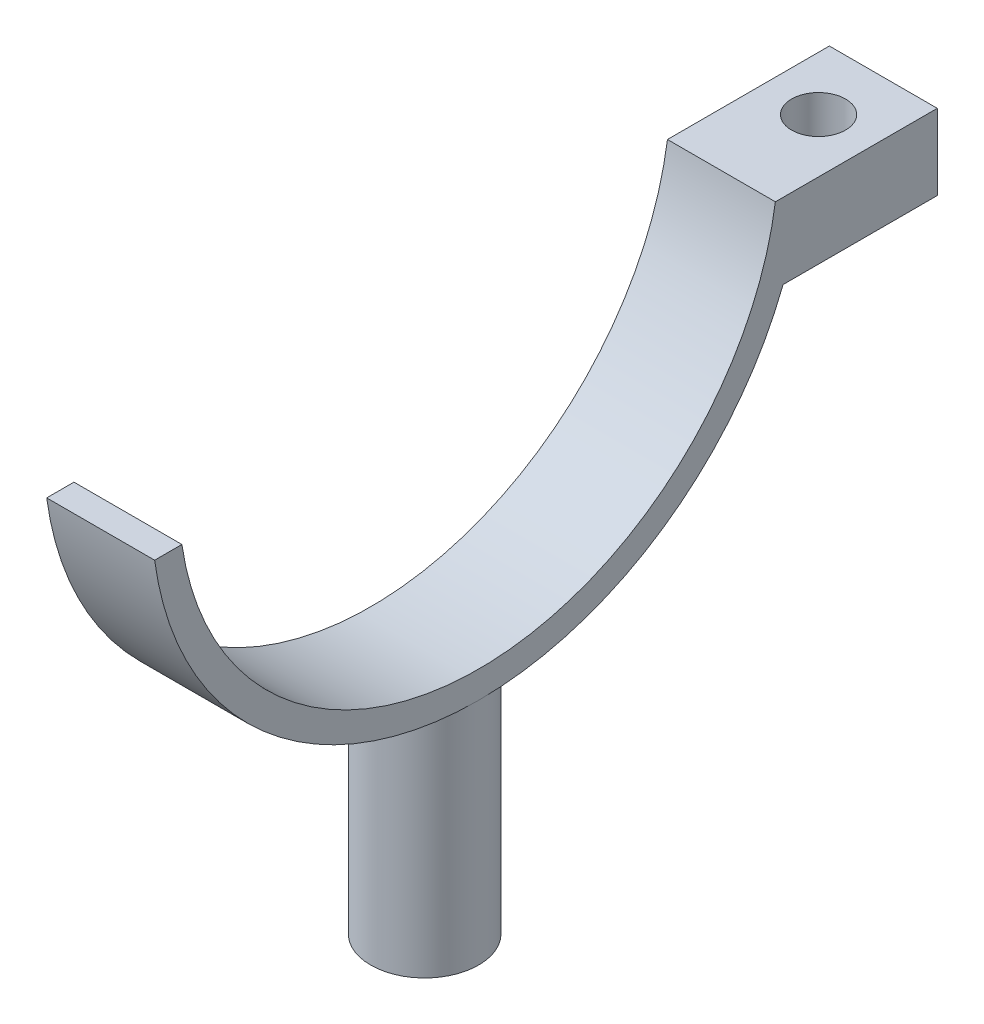
SolidWorks part; units mm, degrees
ref_plane "Front Plane" through (0, 0, 0) normal (0, 0, 1) x (1, 0, 0)
ref_plane "Top Plane" through (0, 0, 0) normal (0, 1, 0) x (1, 0, 0)
ref_plane "Right Plane" through (0, 0, 0) normal (1, 0, 0) x (0, 0, -1)
sketch "Sketch1" plane through (0, 0, 0) normal (0, 1, 0) x (1, 0, 0)
  circle A0 centre (0, 0) radius 5
  dimension "D1" = 10
extrude "Boss-Extrude1" add sketch "Sketch1" along normal blind 23.5
sketch "Sketch2" plane through (0, 0, 0) normal (1, 0, 0) x (0, 0, -1)
  line L0 (-30.0173, 47.5) -> (-27.4927, 47.5)
  line L1 (27.4927, 47.5) -> (30.0173, 47.5)
  line L2 (5, 23.5) -> (-5, 23.5) construction
  arc A0 (-27.4927, 47.5) -> (27.4927, 47.5) centre (0, 51.5376) ccw
  arc A1 (-30.0173, 47.5) -> (30.0173, 47.5) centre (0, 51.5376) ccw
  point P6 (0, 21.25)
  point P7 (0, 51.5376)
  dimension "D1" = 55.5752
  dimension "D3" = 60.5752
  dimension "D2" = 2.25
  dimension "D4" = 47.5
extrude "Boss-Extrude2" add sketch "Sketch2" along normal mid plane 10
sketch "Sketch3" plane through (0, 47.5, 0) normal (0, 1, 0) x (1, 0, 0)
  line L1 (-5, 27.4927) -> (5, 27.4927)
  line L2 (-5, 27.4927) -> (-5, 42.4927)
  line L3 (-5, 42.4927) -> (5, 42.4927)
  line L4 (5, 27.4927) -> (5, 42.4927)
  circle A0 centre (0, 36.4927) radius 2.5
  dimension "D5" = 5
  dimension "D1" = 15
  dimension "D2" = 10
  dimension "D3" = 9
  dimension "D4" = 5
extrude "Boss-Extrude3" add sketch "Sketch3" against normal blind 7
